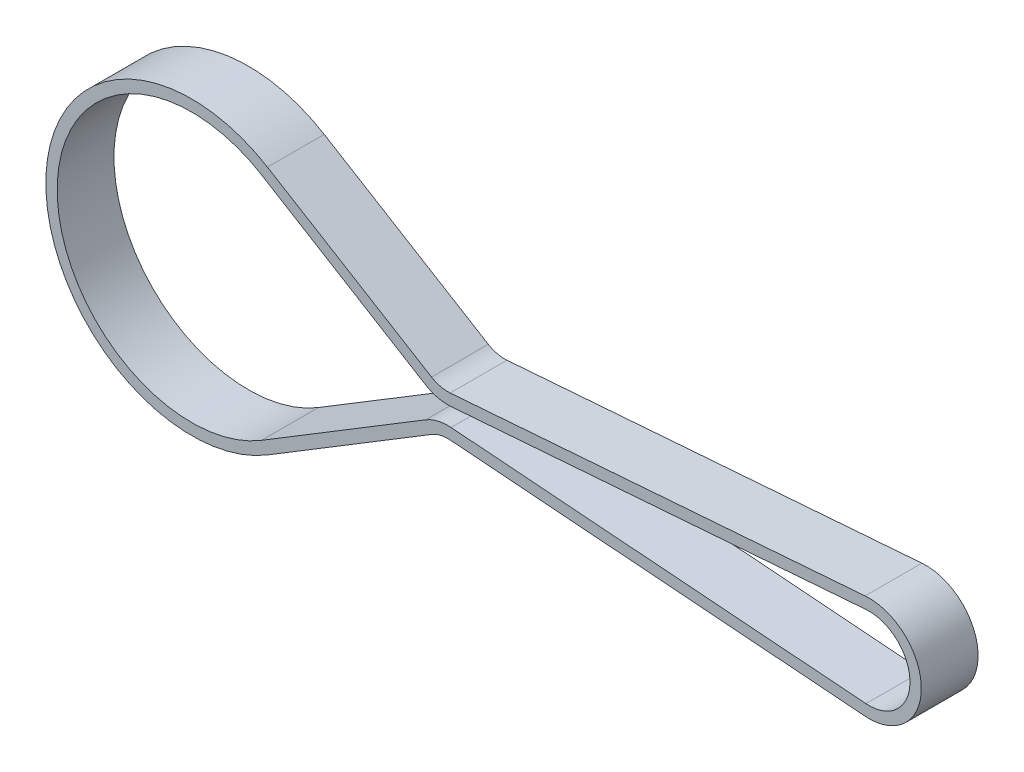
SolidWorks part; units mm, degrees
ref_plane "Front Plane" through (0, 0, 0) normal (0, 0, 1) x (1, 0, 0)
ref_plane "Top Plane" through (0, 0, 0) normal (0, 1, 0) x (1, 0, 0)
ref_plane "Right Plane" through (0, 0, 0) normal (1, 0, 0) x (0, 0, -1)
sketch "Sketch2" plane through (0, 0, 0) normal (0, 0, 1) x (1, 0, 0)
  line L0 (0, 0) -> (1, 0) construction
  line L1 (0, 0) -> (0, 1) construction
  line L2 (-3.1541, 5.1862) -> (-34.9478, -14.1496)
  line L5 (80.8695, -0.0955) -> (0.4628, 6.0523)
  line L8 (0.4628, 13.9477) -> (80.8695, 20.0955)
  line L11 (-34.9478, 34.1496) -> (-3.1541, 14.8138)
  arc A0 (0.4628, 6.0523) -> (-3.1541, 5.1862) centre (0, 0) ccw
  arc A1 (-34.9478, -14.1496) -> (-34.9478, 34.1496) centre (-49.6348, 10) cw
  arc A3 (80.8695, 20.0955) -> (80.8695, -0.0955) centre (81.6414, 10) cw
  arc A5 (-3.1541, 14.8138) -> (0.4628, 13.9477) centre (0, 20) ccw
extrude "Extrude-Thin1" add sketch "Sketch2" along normal up to surface (5.3 mm away) and the other way up to surface (5.7 mm away) thin
